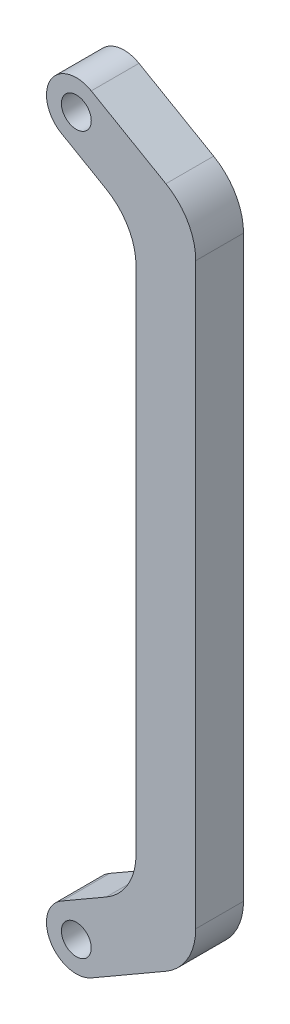
SolidWorks part; units mm, degrees
material "Vero PureWhite"
ref_plane "前视基准面" through (0, 0, 0) normal (0, 0, 1) x (1, 0, 0)
ref_plane "上视基准面" through (0, 0, 0) normal (0, 1, 0) x (1, 0, 0)
ref_plane "右视基准面" through (0, 0, 0) normal (1, 0, 0) x (0, 0, -1)
other "Configuration Table"
sketch "草图1" plane through (0, 0, 0) normal (0, 0, 1) x (1, 0, 0)
  line L0 (0, 120) -> (0, 0) construction
  circle A2 centre (0, 120) radius 5
  circle A3 centre (0, 0) radius 5.0013
  dimension "D4" = 10
  dimension "D5" = 10.0025
extrude "凸台-拉伸1" add sketch "草图1" along normal blind 8
sketch "草图4" plane through (0, 0, 0) normal (0, 0, 1) x (1, 0, 0)
  line L0 (0, 120) -> (0, 0) construction
  line L1 (0, 120) -> (15, 111.3397)
  line L2 (15, 111.3397) -> (15, 8.6603)
  line L3 (15, 8.6603) -> (0, 0)
  dimension "D1" = 15
  dimension "D2" = 60
  dimension "D3" = 60
extrude "拉伸-薄壁4" add sketch "草图4" along normal up to surface (8 mm away) thin up to face at (5, 120, 8) thin type mid plane wall 10
sketch "草图5" plane through (0, 0, 8) normal (0, 0, 1) x (1, 0, 0)
  circle A0 centre (0, 120) radius 2.5
  circle A1 centre (0, 0) radius 2.5
  dimension "D1" = 5
  dimension "D2" = 5
extrude "切除-拉伸2" cut sketch "草图5" against normal through all
fillet "圆角1" radius 10 4 edges at (10, 108.453, 4) (10, 11.547, 4) (20, 5.7735, 4) (20, 114.2265, 4)
